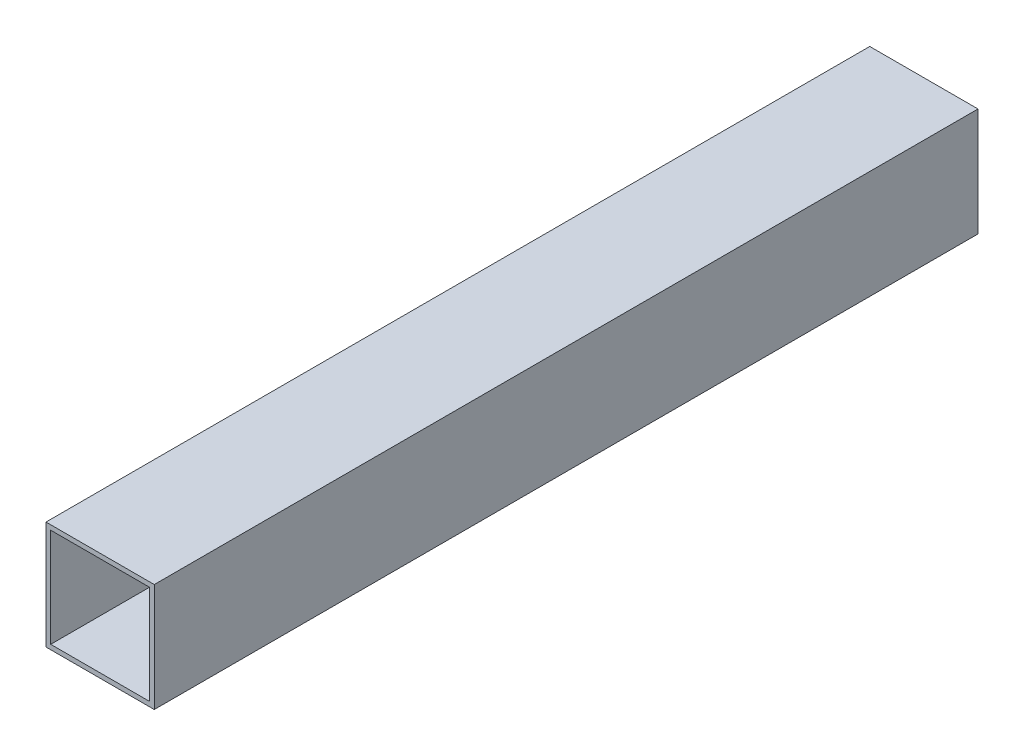
SolidWorks part; units mm, degrees
ref_plane "Plano frontal" through (0, 0, 0) normal (0, 0, 1) x (1, 0, 0)
ref_plane "Plano superior" through (0, 0, 0) normal (0, 1, 0) x (1, 0, 0)
ref_plane "Plano direito" through (0, 0, 0) normal (1, 0, 0) x (0, 0, -1)
sketch "Esboço1" plane through (0, 0, 0) normal (0, 0, 1) x (1, 0, 0)
  line L0 (2, 2) -> (2, 44)
  line L1 (0, 0) -> (46, 0)
  line L2 (0, 0) -> (0, 46)
  line L3 (0, 46) -> (46, 46)
  line L4 (46, 0) -> (46, 46)
  line L5 (2, 44) -> (44, 44)
  line L6 (44, 2) -> (44, 44)
  line L7 (2, 2) -> (44, 2)
  dimension "D1" = 46
  dimension "D2" = 46
  dimension "D3" = 2
extrude "Ressalto-extrusão1" add sketch "Esboço1" along normal blind 350
